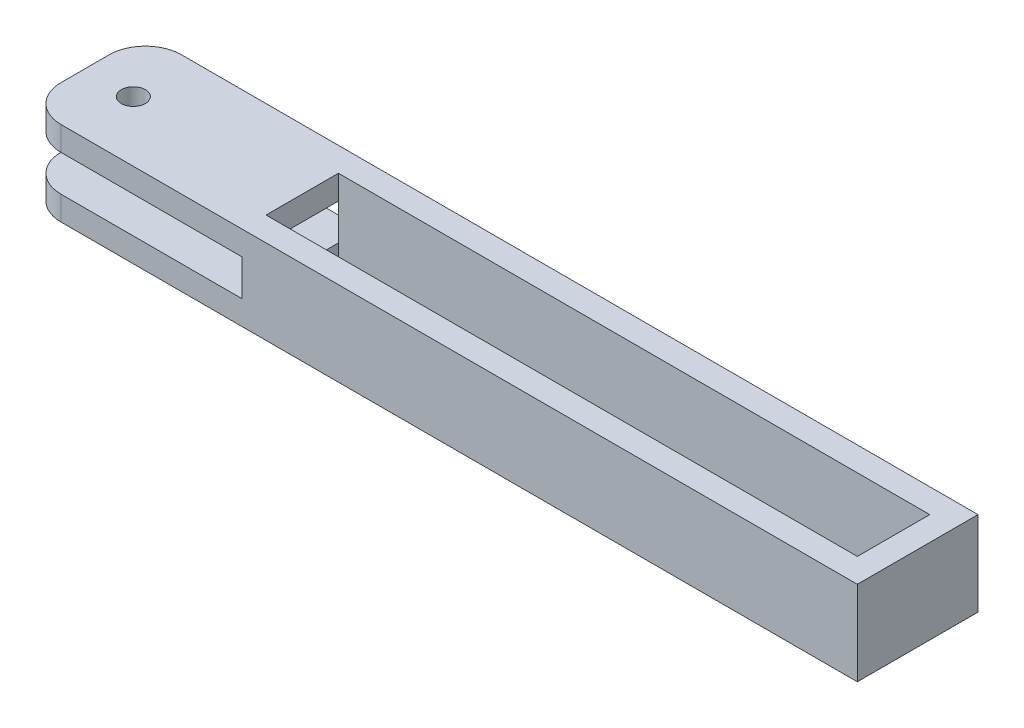
SolidWorks part; units mm, degrees
ref_plane "Front Plane" through (0, 0, 0) normal (0, 0, 1) x (1, 0, 0)
ref_plane "Top Plane" through (0, 0, 0) normal (0, 1, 0) x (1, 0, 0)
ref_plane "Right Plane" through (0, 0, 0) normal (1, 0, 0) x (0, 0, -1)
sketch "Sketch1" plane through (0, 0, 0) normal (0, 0, 1) x (1, 0, 0)
  line L0 (-345, 25) -> (-255, 25)
  line L1 (0, 0) -> (-345, 0)
  line L2 (0, 0) -> (0, 35)
  line L3 (0, 35) -> (-345, 35)
  line L4 (-345, 0) -> (-345, 10)
  line L5 (-255, 25) -> (-255, 10)
  line L6 (-255, 10) -> (-345, 10)
  line L7 (-350, 17.5) -> (0, 17.5) construction
  line L8 (-345, 25) -> (-345, 35)
  point P11 (-255, 17.5)
  dimension "D1" = 345
  dimension "D2" = 35
  dimension "D3" = 255
  dimension "D4" = 15
extrude "Boss-Extrude1" add sketch "Sketch1" along normal blind 50
sketch "Sketch2" plane through (0, 35, 0) normal (0, 1, 0) x (1, 0, 0)
  line L0 (0, -50) -> (0, 0) construction
  line L1 (-255, -10) -> (-10, -10)
  line L2 (-255, -10) -> (-255, -40)
  line L3 (-255, -40) -> (-10, -40)
  line L4 (-10, -10) -> (-10, -40)
  line L5 (0, -25) -> (-345, -25) construction
  line L6 (-345, -50) -> (-345, 0) construction
  circle A0 centre (-325, -25) radius 5
  point P10 (-10, -25)
  dimension "D4" = 10
  dimension "D1" = 10
  dimension "D2" = 255
  dimension "D3" = 30
  dimension "D5" = 20
extrude "Cut-Extrude1" cut sketch "Sketch2" against normal through all
fillet "Fillet1" radius 15 4 edges at (-345, 5, 50) (-345, 30, 50) (-345, 5, 0) (-345, 30, 0)
